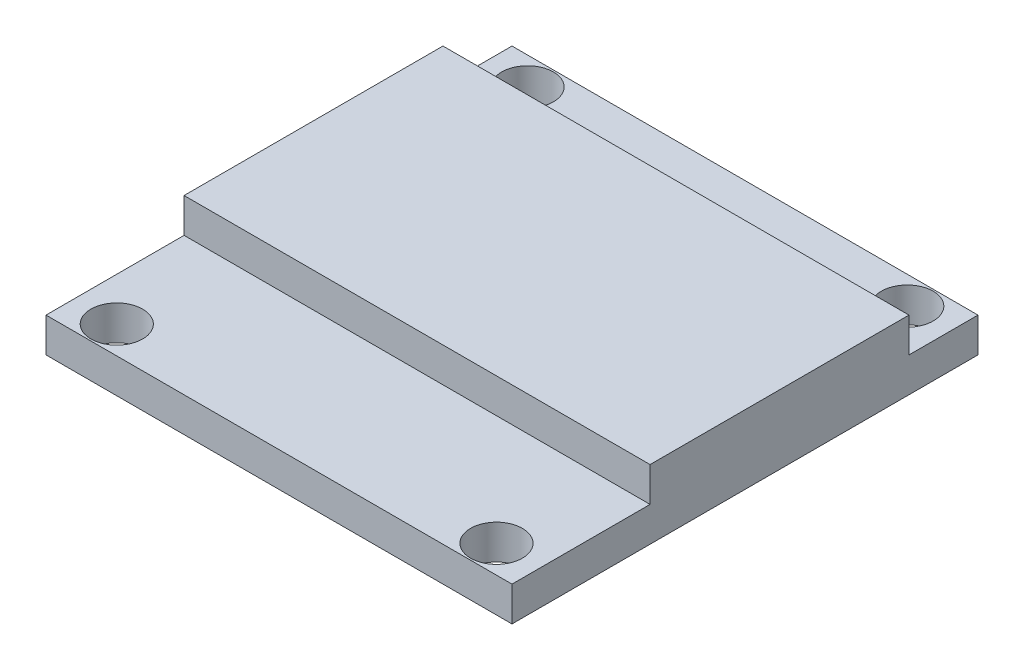
SolidWorks part; units mm, degrees
ref_plane "Front Plane" through (0, 0, 0) normal (0, 0, 1) x (1, 0, 0)
ref_plane "Top Plane" through (0, 0, 0) normal (0, 1, 0) x (1, 0, 0)
ref_plane "Right Plane" through (0, 0, 0) normal (1, 0, 0) x (0, 0, -1)
sketch "Sketch1" plane through (0, 0, 0) normal (0, 1, 0) x (1, 0, 0)
  line L0 (13.5, 27) -> (13.5, 0) construction
  line L1 (0, 0) -> (27, 0)
  line L2 (0, 0) -> (0, 27)
  line L3 (0, 27) -> (27, 27)
  line L4 (27, 0) -> (27, 27)
  line L5 (0, 13.5) -> (27, 13.5) construction
  circle A0 centre (2.5, 25.4) radius 1.5
  circle A1 centre (24.5, 25.4) radius 1.5
  circle A2 centre (24.5, 1.6) radius 1.5
  circle A3 centre (2.5, 1.6) radius 1.5
  point P11 (3.4374, 24.222)
  point P12 (0, 0)
  dimension "D3" = 3
  dimension "D1" = 27
  dimension "D2" = 27
  dimension "D4" = 2.5
  dimension "D5" = 1.6
extrude "Boss-Extrude1" add sketch "Sketch1" along normal blind 2
sketch "Sketch2" plane through (0, 2, 0) normal (0, 1, 0) x (1, 0, 0)
  line L0 (0, 27) -> (0, 0) construction
  line L1 (0, 23) -> (27, 23)
  line L2 (0, 23) -> (0, 8)
  line L3 (0, 8) -> (27, 8)
  line L4 (27, 23) -> (27, 8)
  line L5 (27, 0) -> (27, 27) construction
  line L6 (27, 27) -> (0, 27) construction
  dimension "D1" = 15
  dimension "D2" = 4
extrude "Boss-Extrude2" add sketch "Sketch2" along normal blind 2
